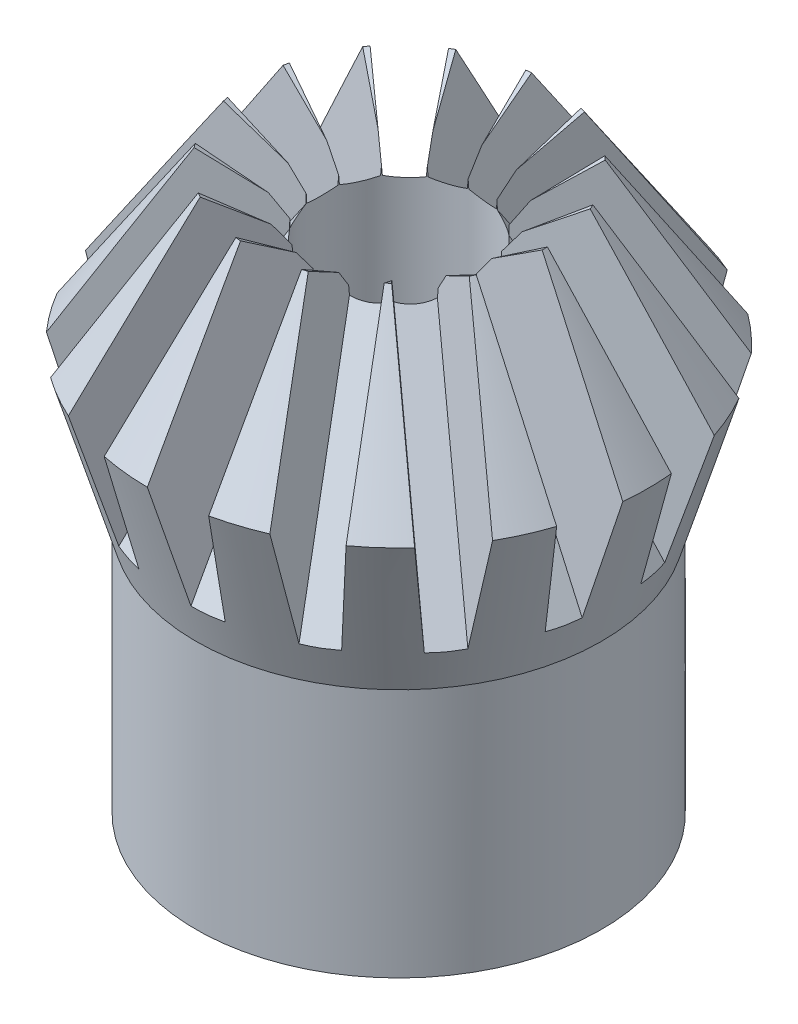
SolidWorks part; units mm, degrees
ref_plane "前视基准面" through (0, 0, 0) normal (0, 0, 1) x (1, 0, 0)
ref_plane "上视基准面" through (0, 0, 0) normal (0, 1, 0) x (1, 0, 0)
ref_plane "右视基准面" through (0, 0, 0) normal (1, 0, 0) x (0, 0, -1)
sketch "草图2" plane through (0, 0, 0) normal (1, 0, 0) x (0, 0, -1)
  line L0 (0, 0) -> (0, 18.3529) construction
  line L1 (2.5, 0) -> (6.5, 0)
  line L2 (6.5, 0) -> (6.5, 8)
  line L3 (6.5, 8) -> (8, 13)
  line L4 (8, 13) -> (4.6834, 18)
  line L5 (4.6834, 18) -> (2.5, 16.5517)
  line L6 (2.5, 16.5517) -> (2.5, 0)
  point P5 (6.5, 9.4709)
  dimension "D1" = 6.5
  dimension "D2" = 2.5
  dimension "D3" = 13
  dimension "D4" = 18
  dimension "D5" = 8
  dimension "D6" = 6
  dimension "D7" = 8
revolve "旋转1" add sketch "草图2" angle 360 about L0
ref_plane "基准面2" through (6.8605, 10.3426, 0) normal (0.5528, 0.8333, 0) x (0.8333, -0.5528, 0)
sketch "草图4" plane through (6.8605, 10.3426, 0) normal (0.5528, 0.8333, 0) x (0.8333, -0.5528, 0)
  line L0 (0, 0) -> (-17.7012, 0) construction
  line L1 (-10.8527, -0.5) -> (-10.8527, 0.5)
  line L2 (-10.8527, 0.5) -> (-13.8527, 0.9)
  line L3 (-13.8527, 0.9) -> (-13.8527, -0.9)
  line L4 (-10.8527, -0.5) -> (-13.8527, -0.9)
  ellipse E0 centre (-9.9499, 0) end of major axis (-9.9499, -4.6834) minor radius 3.9028 construction
  point P14 (-10.8527, 0)
  point P15 (-13.8527, 0)
  dimension "D1" = 0.9
  dimension "D2" = 0.5
  dimension "D3" = 3
extrude "切除-拉伸2" cut sketch "草图4" against normal up to next and the other way up to next
pattern_circular "阵列(圆周)1" count 15 over 360 about axis through (0, 0, 0) along (0, 1, 0) of "切除-拉伸2"
sketch "草图5" plane through (0, 0, 0) normal (0, 0, 1) x (1, 0, 0)
  line L0 (-6.5, 0) -> (6.5, 0) construction
  circle A0 centre (0, 4) radius 2
  dimension "D1" = 4
  dimension "D2" = 4
extrude "切除-拉伸3" cut sketch "草图5" against normal up to next
